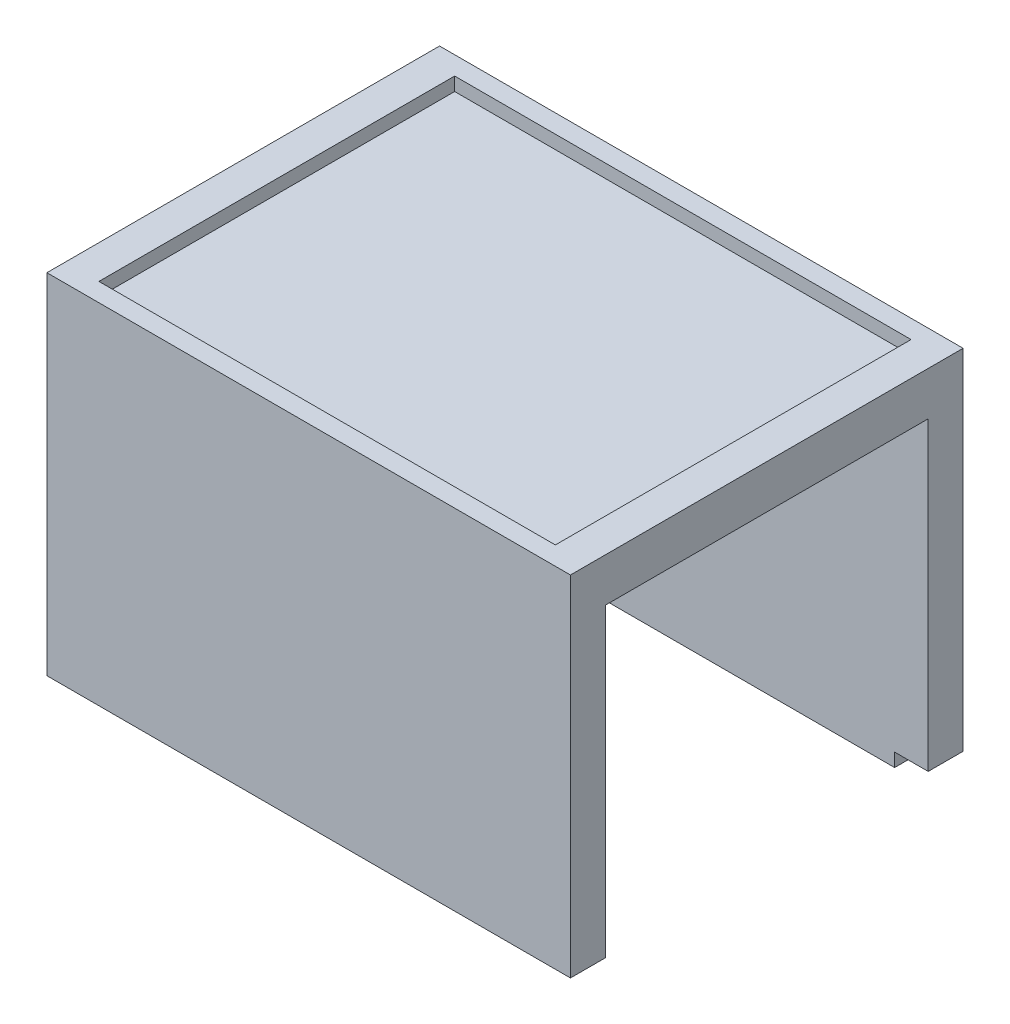
SolidWorks part; units mm, degrees
ref_plane "Front Plane" through (0, 0, 0) normal (0, 0, 1) x (1, 0, 0)
ref_plane "Top Plane" through (0, 0, 0) normal (0, 1, 0) x (1, 0, 0)
ref_plane "Right Plane" through (0, 0, 0) normal (1, 0, 0) x (0, 0, -1)
sketch "Sketch1" plane through (0, 0, 0) normal (0, 1, 0) x (1, 0, 0)
  line L1 (-19.5, 14.625) -> (19.5, 14.625)
  line L2 (-19.5, 14.625) -> (-19.5, -14.625)
  line L3 (-19.5, -14.625) -> (19.5, -14.625)
  line L4 (19.5, 14.625) -> (19.5, -14.625)
  line L5 (-19.5, 14.625) -> (19.5, -14.625) construction
  line L6 (-19.5, -14.625) -> (19.5, 14.625) construction
  point P0 (0, 0)
  dimension "D1" = 39
  dimension "D2" = 29.25
extrude "Boss-Extrude1" add sketch "Sketch1" along normal blind 3.25
sketch "Sketch2" plane through (0, 3.25, 0) normal (0, 1, 0) x (1, 0, 0)
  line L1 (-17, 12) -> (17, 12)
  line L2 (-17, 12) -> (-17, -12)
  line L3 (-17, -12) -> (17, -12)
  line L4 (17, 12) -> (17, -12)
  line L5 (-17, 12) -> (17, -12) construction
  line L6 (-17, -12) -> (17, 12) construction
  point P0 (0, 0)
  dimension "D1" = 34
  dimension "D2" = 24
extrude "Cut-Extrude1" cut sketch "Sketch2" against normal blind 1
sketch "Sketch3" plane through (0, 3.25, 0) normal (0, 1, 0) x (1, 0, 0)
  line L0 (-17, -12) -> (17, -12) construction
  line L1 (-17, -12) -> (17, -12)
  line L2 (-17, -12) -> (-17, -13.25)
  line L3 (-17, -13.25) -> (17, -13.25)
  line L4 (17, -12) -> (17, -13.25)
  line L5 (-17, -12) -> (17, -13.25) construction
  line L6 (-17, -13.25) -> (17, -12) construction
  line L7 (-17, 12) -> (-17, -12) construction
  point P0 (0, -12.625)
  dimension "D1" = 1.25
extrude "Cut-Extrude2" cut sketch "Sketch3" against normal blind 1
mirror "Mirror1" about plane through (0, 0, 0) normal (0, 0, 1) of "Cut-Extrude2"
sketch "Sketch4" plane through (0, 0, 14.625) normal (0, 0, 1) x (1, 0, 0)
  line L0 (-19.5, 0) -> (19.5, 0) construction
  line L1 (-19.5, 0) -> (19.5, 0)
  line L2 (-19.5, 0) -> (-19.5, -22.75)
  line L3 (-19.5, -22.75) -> (19.5, -22.75)
  line L4 (19.5, 0) -> (19.5, -22.75)
  line L5 (-19.5, 0) -> (19.5, -22.75) construction
  line L6 (-19.5, -22.75) -> (19.5, 0) construction
  line L7 (-19.5, 3.25) -> (-19.5, 0) construction
  point P0 (0, -11.375)
  dimension "D1" = 22.75
extrude "Boss-Extrude2" add sketch "Sketch4" against normal blind 2.6
sketch "Sketch6" plane through (0, -22.75, 0) normal (0, -1, 0) x (1, 0, 0)
  line L0 (-19.5, 12.025) -> (19.5, 12.025) construction
  line L1 (-17, 13.275) -> (17, 13.275)
  line L2 (-17, 13.275) -> (-17, 12.025)
  line L3 (-17, 12.025) -> (17, 12.025)
  line L4 (17, 13.275) -> (17, 12.025)
  line L5 (-17, 13.275) -> (17, 12.025) construction
  line L6 (-17, 12.025) -> (17, 13.275) construction
  point P0 (0, 12.65)
  point P5 (0, 0)
  dimension "D1" = 1.25
  dimension "D2" = 34
extrude "Boss-Extrude3" add sketch "Sketch6" along normal blind 1
mirror "Mirror2" about plane through (0, 0, 0) normal (0, 0, 1) of "Boss-Extrude3", "Boss-Extrude2"
